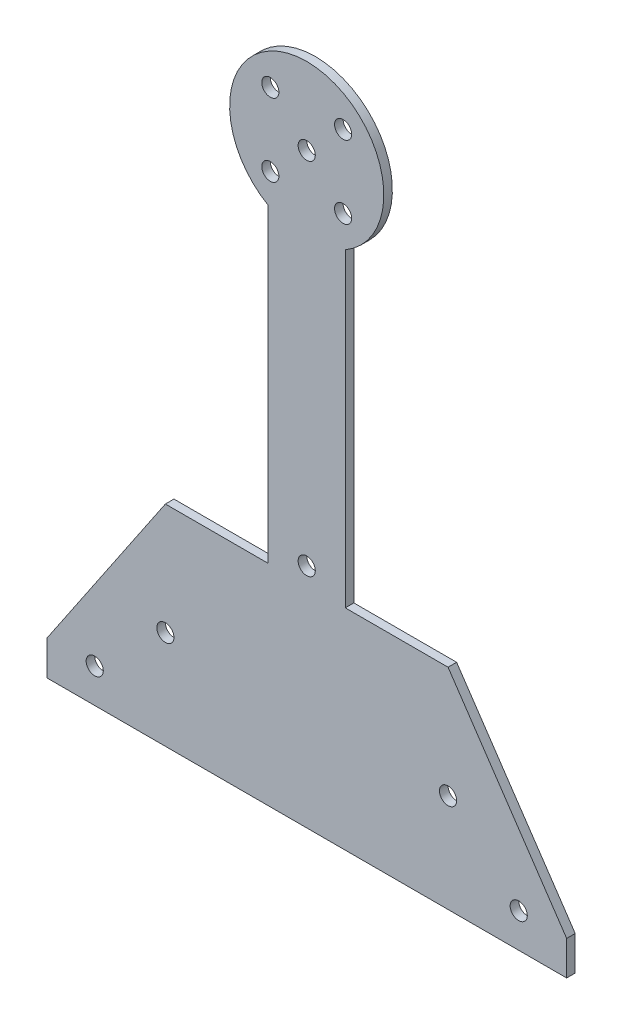
SolidWorks part; units mm, degrees
ref_plane "前视基准面" through (0, 0, 0) normal (0, 0, 1) x (1, 0, 0)
ref_plane "上视基准面" through (0, 0, 0) normal (0, 1, 0) x (1, 0, 0)
ref_plane "右视基准面" through (0, 0, 0) normal (1, 0, 0) x (0, 0, -1)
sketch "草图1" plane through (0, 0, 0) normal (0, 0, 1) x (1, 0, 0)
  line L0 (-49.7914, -7.3543) -> (-16.7914, -7.3543) construction
  line L1 (-33.2914, -7.3543) -> (-33.2914, 7.6457) construction
  line L2 (-0.2914, 7.6457) -> (-0.2914, 121.6457) construction
  line L3 (-0.2914, 121.6457) -> (5.7086, 121.6457) construction
  line L4 (-9.2914, 33.6457) -> (-9.2914, 106.0573)
  line L5 (-9.2914, 33.6457) -> (-33.2914, 33.6457)
  line L6 (-33.2914, 33.6457) -> (-60.9865, -7.3543)
  line L7 (-60.9865, -7.3543) -> (-60.9865, -15.3543)
  line L8 (-60.9865, -15.3543) -> (0, -15.3543)
  line L9 (60.4036, -15.3543) -> (-0.5829, -15.3543)
  line L10 (60.4036, -7.3543) -> (60.4036, -15.3543)
  line L11 (32.7086, 33.6457) -> (60.4036, -7.3543)
  line L12 (8.7086, 33.6457) -> (32.7086, 33.6457)
  line L13 (8.7086, 33.6457) -> (8.7086, 106.0573)
  line L14 (-0.2914, 121.6457) -> (-0.2914, 130.1457) construction
  line L15 (-0.2914, 130.1457) -> (8.2086, 130.1457) construction
  circle A0 centre (16.2086, -7.3543) radius 2 construction
  circle A1 centre (-16.7914, -7.3543) radius 2 construction
  circle A2 centre (49.2086, -7.3543) radius 2
  circle A3 centre (-49.7914, -7.3543) radius 2
  circle A4 centre (-33.2914, 7.6457) radius 2
  circle A5 centre (32.7086, 7.6457) radius 2
  circle A6 centre (-0.2914, 7.6457) radius 2 construction
  circle A11 centre (8.2086, 130.1457) radius 2
  circle A12 centre (-0.2914, 37.6457) radius 2
  circle A13 centre (8.2086, 113.1457) radius 2
  circle A14 centre (-8.7914, 113.1457) radius 2
  circle A15 centre (-8.7914, 130.1457) radius 2
  circle A16 centre (-0.2914, 121.6457) radius 18 construction
  arc A17 (-9.2914, 106.0573) -> (8.7086, 106.0573) centre (-0.2914, 121.6457) cw
  circle A18 centre (-0.2914, 121.6457) radius 2
  text T0 "<b>RF</b>" font "@Adobe 明體 Std L" height 9.5
  dimension "D1" = 114
  dimension "D5" = 30
  dimension "D6" = 4
  dimension "D7" = 4
  dimension "D8" = 8
  dimension "D2" = 24
  dimension "D4" = 8
  dimension "D9" = 137
extrude "凸台-拉伸1" add sketch "草图1" along normal blind 2
